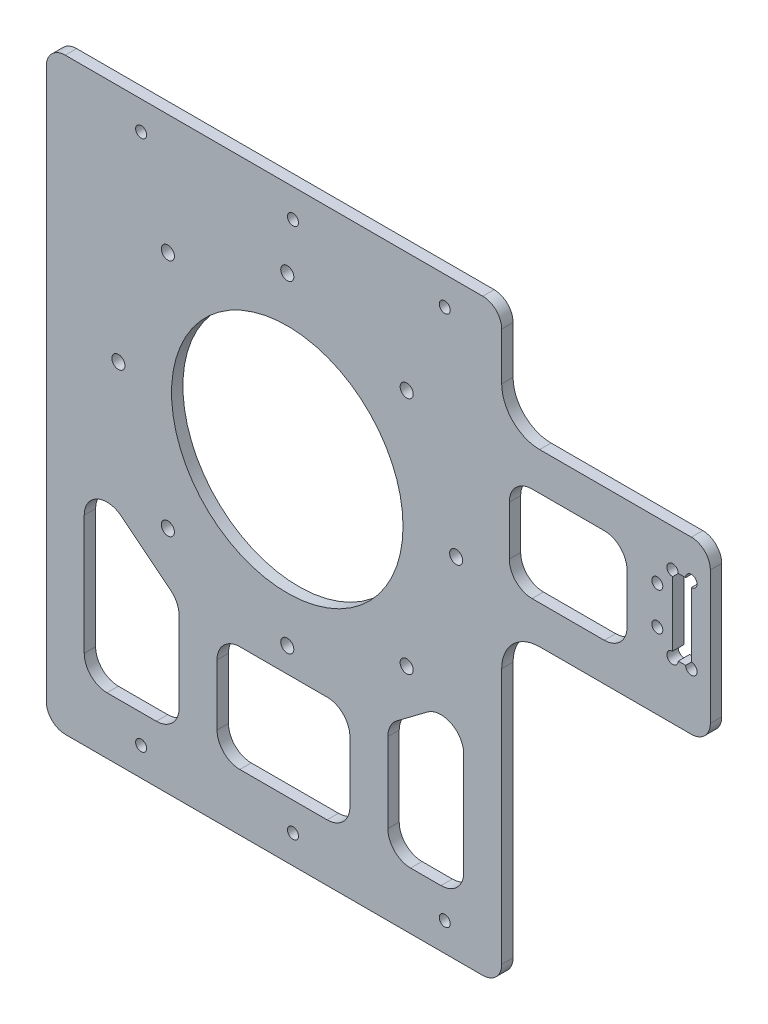
SolidWorks part; units mm, degrees
material "Thornel Mat VMA"
ref_plane "前视基准面" through (0, 0, 0) normal (0, 0, 1) x (1, 0, 0)
ref_plane "上视基准面" through (0, 0, 0) normal (0, 1, 0) x (1, 0, 0)
ref_plane "右视基准面" through (0, 0, 0) normal (1, 0, 0) x (0, 0, -1)
sketch "草图1" plane through (0, 0, 0) normal (0, 0, 1) x (1, 0, 0)
  line L0 (0, 7.5) -> (-120, 7.5) construction
  line L1 (0, 0) -> (-120, 0)
  line L2 (0, 0) -> (0, 155)
  line L3 (0, 155) -> (-120, 155)
  line L4 (-120, 0) -> (-120, 155)
  line L5 (0, 77.5) -> (-319.2534, 77.5) construction
  line L6 (0, 147.5) -> (-120, 147.5) construction
  line L7 (-56.5, 49.5) -> (-56.5, 134.5) construction
  line L8 (-87.9663, 123.4663) -> (-56.5, 92) construction
  line L9 (-56.5, 92) -> (-25.0337, 60.5337) construction
  line L10 (41, 102.5) -> (41, 112.5) construction
  line L11 (0, 127.5) -> (54.975, 127.5)
  line L12 (0, 127.5) -> (0, 82.5)
  line L13 (0, 82.5) -> (54.975, 82.5)
  line L14 (-87.9663, 60.5337) -> (-56.5, 92) construction
  line L15 (-56.5, 92) -> (-25.0337, 123.4663) construction
  line L16 (54.975, 127.5) -> (54.975, 82.5)
  line L17 (45.025, 97.5) -> (49.975, 97.5)
  line L18 (45.025, 97.5) -> (45.025, 117.5)
  line L19 (45.025, 117.5) -> (49.975, 117.5)
  line L20 (49.975, 97.5) -> (49.975, 117.5)
  line L21 (45.025, 97.5) -> (49.975, 117.5) construction
  line L22 (45.025, 117.5) -> (49.975, 97.5) construction
  line L23 (-110, 65) -> (-110, 15)
  line L24 (-110, 15) -> (-85, 15)
  line L25 (-85, 15) -> (-85, 45)
  line L26 (-85, 45) -> (-110, 65)
  line L27 (-75, 43) -> (-75, 15)
  line L28 (-75, 15) -> (-40, 15)
  line L29 (-40, 15) -> (-40, 43)
  line L30 (-40, 43) -> (-75, 43)
  line L31 (-10, 60) -> (-10, 15)
  line L32 (-10, 15) -> (-30, 15)
  line L33 (-30, 15) -> (-30, 45)
  line L34 (-30, 45) -> (-10, 60)
  circle A0 centre (-15, 7.5) radius 1.45
  circle A1 centre (-55, 7.5) radius 1.45
  circle A2 centre (-15, 147.5) radius 1.45
  circle A3 centre (-55, 147.5) radius 1.45
  circle A4 centre (-56.5, 92) radius 30.5
  circle A5 centre (-56.5, 92) radius 44.5 construction
  circle A6 centre (-56.5, 134.5) radius 1.725
  circle A7 centre (-56.5, 49.5) radius 1.725
  circle A8 centre (-87.9663, 123.4663) radius 1.725
  circle A9 centre (-87.9663, 60.5337) radius 1.725
  circle A10 centre (-25.0337, 60.5337) radius 1.725
  circle A11 centre (-25.0337, 123.4663) radius 1.725
  circle A12 centre (-12, 92) radius 1.725
  circle A13 centre (-101, 92) radius 1.725
  circle A14 centre (41, 102.5) radius 1.45
  circle A15 centre (41, 112.5) radius 1.45
  circle A16 centre (-95, 7.5) radius 1.45
  circle A17 centre (-95, 147.5) radius 1.45
  point P19 (0, 77.5)
  point P26 (-56.5, 92)
  point P44 (47.5, 107.5)
  dimension "D4" = 2.9
  dimension "D7" = 89
  dimension "D8" = 61
  dimension "D12" = 3.45
  dimension "D23" = 2.9
  dimension "D1" = 155
  dimension "D2" = 15
  dimension "D3" = 40
  dimension "D5" = 7.5
  dimension "D6" = 85
  dimension "D9" = 63
  dimension "D10" = 45
  dimension "D11" = 45
  dimension "D13" = 56.5
  dimension "D14" = 120
  dimension "D15" = 47.5
  dimension "D16" = 30
  dimension "D17" = 90
  dimension "D18" = 4.95
  dimension "D19" = 10
  dimension "D20" = 15
  dimension "D21" = 5
  dimension "D22" = 6.5
  dimension "D24" = 5
  dimension "D25" = 10
  dimension "D26" = 10
  dimension "D27" = 15
  dimension "D28" = 10
  dimension "D29" = 10
  dimension "D30" = 10
  dimension "D31" = 28
  dimension "D32" = 35
  dimension "D33" = 30
  dimension "D34" = 45
  dimension "D35" = 50
  dimension "D36" = 30
  dimension "D37" = 30
  dimension "D38" = 40
extrude "凸台-拉伸1" add sketch "草图1" along normal blind 3 contours L16 L11 L2 L13 L20 L17 L18 L19 | L4 L1 L2 L3 A13 A12 A11 A10 A9 A8 A7 A6 A4 A2 A1 A0 A3
fillet "圆角1" radius 6 12 edges at (-75, 43, 1.5) (-75, 15, 1.5) (-40, 15, 1.5) (-40, 43, 1.5) (-110, 65, 1.5) (-85, 15, 1.5) (-85, 45, 1.5) (-30, 15, 1.5) (-10, 15, 1.5) (-10, 60, 1.5) (-30, 45, 1.5) (-110, 15, 1.5)
fillet "圆角2" radius 10 2 edges at (0, 127.5, 1.5) (0, 82.5, 1.5)
sketch "草图2" plane through (0, 0, 3) normal (0, 0, 1) x (1, 0, 0)
  line L0 (10, 127.5) -> (54.975, 127.5) construction
  line L1 (2, 117.5) -> (33.025, 117.5)
  line L2 (2, 117.5) -> (2, 92.5)
  line L3 (2, 92.5) -> (33.025, 92.5)
  line L4 (33.025, 117.5) -> (33.025, 92.5)
  line L5 (10, 82.5) -> (54.975, 82.5) construction
  line L6 (45.025, 97.5) -> (45.025, 117.5) construction
  line L7 (0, 137.5) -> (0, 155) construction
  dimension "D1" = 10
  dimension "D2" = 10
  dimension "D3" = 12
  dimension "D4" = 2
extrude "切除-拉伸1" cut sketch "草图2" against normal through all
fillet "圆角3" radius 6 4 edges at (33.025, 117.5, 1.5) (33.025, 92.5, 1.5) (2, 92.5, 1.5) (2, 117.5, 1.5)
fillet "圆角4" radius 5 6 edges at (0, 0, 1.5) (-120, 0, 1.5) (-120, 155, 1.5) (0, 155, 1.5) (54.975, 127.5, 1.5) (54.975, 82.5, 1.5)
sketch "草图3" plane through (0, 0, 3) normal (0, 0, 1) x (1, 0, 0)
  circle A0 centre (45.025, 117.5) radius 1.5
  circle A1 centre (49.975, 117.5) radius 1.5
  circle A2 centre (45.025, 97.5) radius 1.5
  circle A3 centre (49.975, 97.5) radius 1.5
  dimension "D1" = 3
extrude "切除-拉伸2" cut sketch "草图3" against normal through all
